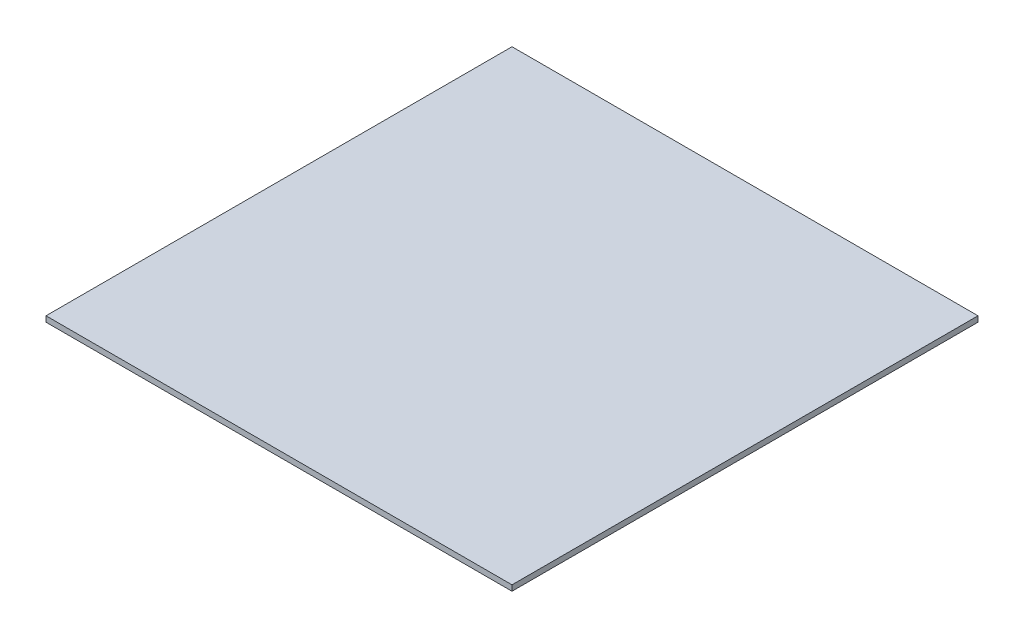
SolidWorks part; units mm, degrees
ref_plane "Alzado" through (0, 0, 0) normal (0, 0, 1) x (1, 0, 0)
ref_plane "Planta" through (0, 0, 0) normal (0, 1, 0) x (1, 0, 0)
ref_plane "Vista lateral" through (0, 0, 0) normal (1, 0, 0) x (0, 0, -1)
sketch "Croquis1" plane through (0, 0, 0) normal (0, 1, 0) x (1, 0, 0)
  line L1 (0, 0) -> (100, 0)
  line L2 (0, 0) -> (0, 100)
  line L3 (0, 100) -> (100, 100)
  line L4 (100, 0) -> (100, 100)
  dimension "D1" = 100
extrude "Saliente-Extruir1" add sketch "Croquis1" along normal blind 1.2
